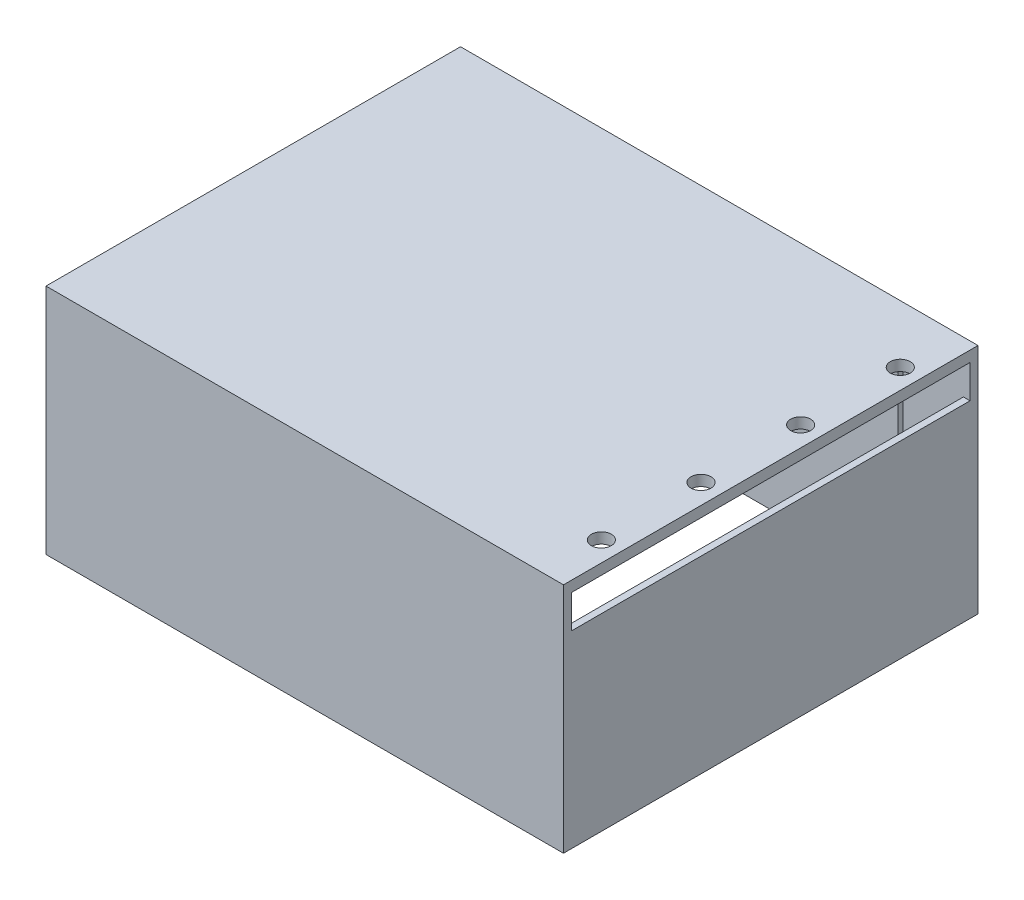
SolidWorks part; units mm, degrees
ref_plane "Front Plane" through (0, 0, 0) normal (0, 0, 1) x (1, 0, 0)
ref_plane "Top Plane" through (0, 0, 0) normal (0, 1, 0) x (1, 0, 0)
ref_plane "Right Plane" through (0, 0, 0) normal (1, 0, 0) x (0, 0, -1)
sketch "Sketch1" plane through (0, 0, 0) normal (0, 1, 0) x (1, 0, 0)
  line L1 (0, 0) -> (77.9, 0)
  line L2 (0, 0) -> (0, 62.4)
  line L3 (0, 62.4) -> (77.9, 62.4)
  line L4 (77.9, 0) -> (77.9, 62.4)
  dimension "D1" = 62.4
  dimension "D2" = 77.9
extrude "Boss-Extrude1" add sketch "Sketch1" along normal blind 35
sketch "Sketch4" plane through (0, 0, 0) normal (0, -1, 0) x (1, 0, 0)
  line L0 (75.9, -2) -> (2, -2)
  line L1 (2, -2) -> (2, -60.4)
  line L2 (2, -60.4) -> (75.9, -60.4)
  line L3 (75.9, -60.4) -> (75.9, -2)
  line L4 (0, 0) -> (0, -62.4)
  line L5 (0, -62.4) -> (77.9, -62.4)
  line L6 (77.9, -62.4) -> (77.9, 0)
  line L7 (77.9, 0) -> (0, 0)
  line L8 (0, 0) -> (0, -62.4)
  line L9 (0, -62.4) -> (77.9, -62.4)
  line L12 (77.9, 0) -> (0, 0) construction
  line L13 (77.9, -62.4) -> (77.9, 0) construction
  dimension "D1" = 0
  dimension "D2" = 2
extrude "Cut-Extrude1" cut sketch "Sketch4" against normal blind 33.39 contours L2 L3 L0 L1
sketch "Sketch6" plane through (0, 35, 0) normal (0, 1, 0) x (1, 0, 0)
  line L0 (2, 17.486) -> (16.1749, 17.486)
  line L1 (2, 2) -> (2, 60.4) construction
  line L2 (16.1749, 17.486) -> (16.1749, 7.5348)
  line L3 (16.1749, 7.5348) -> (0, 7.5348)
  line L4 (0, 62.4) -> (0, 0) construction
  line L5 (0, 7.5348) -> (0, 17.486)
  line L6 (0, 17.486) -> (2, 17.486)
sketch "Sketch7" plane through (0, 0, 0) normal (-1, 0, 0) x (0, 0, 1)
  line L0 (-48.9, 0) -> (-48.9, 5)
  line L1 (-62.4, 0) -> (0, 0) construction
  line L2 (-48.9, 0) -> (-48.9, -7.25) construction
  line L3 (-62.4, 35) -> (0, 35) construction
  line L5 (-42.3333, 35) -> (-42.3333, 0) construction
  line L6 (-35.7665, 0) -> (-35.7665, 5)
  line L7 (-48.9, 0) -> (-35.7665, 0)
  line L8 (-35.7665, 5) -> (-48.9, 5)
  dimension "D1" = 5
extrude "Cut-Extrude6" cut sketch "Sketch7" against normal blind 15
sketch "Sketch8" plane through (0, 35, 0) normal (0, 1, 0) x (1, 0, 0)
  circle A0 centre (10.2738, 54.1108) radius 1.75
  dimension "D1" = 3.5
sketch "Sketch9" plane through (0, 33.39, 0) normal (0, -1, 0) x (1, 0, 0)
  circle A0 centre (19.1575, -55.1585) radius 0.8
  circle A1 centre (69.9447, -11.9913) radius 0.8
  circle A2 centre (18.0145, -7.2415) radius 0.8
  circle A3 centre (69.9447, -39.9186) radius 0.8
  dimension "D1" = 1.6
  dimension "D2" = 1.6
  dimension "D3" = 1.6
  dimension "D4" = 1.6
sketch "Sketch11" plane through (0, 0, 0) normal (-1, 0, 0) x (0, 0, 1)
  line L0 (0, 35) -> (0, 0) construction
  line L1 (-17.4865, 0) -> (-7.53, 0)
  line L2 (-17.4865, 0) -> (-17.4865, 5.15)
  line L3 (-17.4865, 5.15) -> (-7.53, 5.15)
  line L4 (-7.53, 0) -> (-7.53, 5.15)
  line L5 (-35.7665, 0) -> (-35.7665, 5) construction
  line L6 (-35.7665, 0) -> (0, 0) construction
  dimension "D1" = 7.53
  dimension "D2" = 18.28
  dimension "D3" = 5.15
extrude "Cut-Extrude8" cut sketch "Sketch11" against normal blind 10
sketch "Sketch12" plane through (0, 0, 0) normal (-1, 0, 0) x (0, 0, 1)
  line L0 (-62.4, 0) -> (-48.9, 0) construction
  line L1 (-52.4, 25) -> (-35.4, 25)
  line L2 (-52.4, 25) -> (-52.4, 9)
  line L3 (-52.4, 9) -> (-35.4, 9)
  line L4 (-35.4, 25) -> (-35.4, 9)
  line L5 (-62.4, 35) -> (-62.4, 0) construction
  dimension "D1" = 9
  dimension "D2" = 16
  dimension "D3" = 17
  dimension "D4" = 10
extrude "Cut-Extrude9" cut sketch "Sketch12" against normal blind 10
sketch "Sketch14" plane through (77.9, 0, 0) normal (1, 0, 0) x (0, 0, -1)
  line L1 (61.2, 33.39) -> (1.2, 33.39)
  line L2 (61.2, 33.39) -> (61.2, 28.39)
  line L3 (61.2, 28.39) -> (1.2, 28.39)
  line L4 (1.2, 33.39) -> (1.2, 28.39)
  line L5 (31.2, 33.39) -> (31.2, 28.39) construction
  line L7 (60.4, 33.39) -> (2, 33.39) construction
  line L8 (31.2, 35) -> (31.2, 12.111) construction
  line L9 (0, 35) -> (62.4, 35) construction
  dimension "D1" = 60
  dimension "D2" = 5
  dimension "D3" = 0
extrude "Cut-Extrude10" cut sketch "Sketch14" against normal blind 10
sketch "Sketch16" plane through (0, 0, 0) normal (0, -1, 0) x (-1, 0, 0)
  line L0 (-77.9, 0) -> (-77.9, 62.4) construction
  line L1 (-67.9, 1.2) -> (-77.9, 1.2) construction
  line L2 (-76.9, 61.2) -> (-67.8234, 61.2)
  line L3 (-76.9, 61.2) -> (-76.9, 1.2)
  line L4 (-76.9, 1.2) -> (-67.8234, 1.2)
  line L5 (-67.8234, 61.2) -> (-67.8234, 1.2)
  line L6 (-67.9, 61.2) -> (-77.9, 61.2) construction
  dimension "D1" = 1
extrude "Cut-Extrude12" cut sketch "Sketch16" against normal up to surface (33.39 mm away)
sketch "Sketch15" plane through (0, 33.39, 0) normal (0, -1, 0) x (-1, 0, 0)
  line L0 (-74.9, 8.7) -> (-74.9, 23.7) construction
  line L1 (-74.9, 16.2) -> (-48.1021, 16.2) construction
  line L2 (-77.9, 31.2) -> (40.2463, 31.2) construction
  line L3 (-77.9, 61.2) -> (-77.9, 1.2) construction
  line L5 (-76.9, 61.2) -> (-76.9, 1.2) construction
  line L6 (-74.9, 38.7) -> (-74.9, 53.7) construction
  line L7 (-74.9, 46.2) -> (-46.556, 46.2) construction
  circle A0 centre (-74.9, 8.7) radius 1.5
  circle A1 centre (-74.9, 23.7) radius 1.5
  circle A2 centre (-74.9, 38.7) radius 1.5
  circle A3 centre (-74.9, 53.7) radius 1.5
  dimension "D1" = 3
  dimension "D2" = 3
  dimension "D4" = 2
  dimension "D5" = 3
  dimension "D6" = 3
  dimension "D7" = 15
  dimension "D3" = 15
  dimension "D8" = 15
  dimension "D9" = 15
extrude "Cut-Extrude11" cut sketch "Sketch15" against normal blind 10
sketch "Sketch17" plane through (2, 0, 0) normal (-1, 0, 0) x (0, 0, 1)
  line L0 (-62.4, 0) -> (0, 0) construction
  line L1 (-31.2, 0) -> (-31.2, 6.6797) construction
  line L2 (-31.2, 3.5) -> (-31.2, 1.5)
  line L3 (-33.7, 0) -> (-28.7, 0)
  line L7 (-33.7, 2.5) -> (-28.7, 2.5) construction
  arc A1 (-31.2, 3.5) -> (-31.2, 1.5) centre (-31.2, 2.5) ccw
  dimension "D1" = 2
sketch "Sketch18" plane through (0, 0, 0) normal (0, -1, 0) x (-1, 0, 0)
  line L0 (-76.9, 61.2) -> (-76.9, 1.2) construction
  line L5 (-76.9, 1.2) -> (-75.2943, 1.2)
  line L6 (-76.9, 1.2) -> (-76.9, 61.2)
  line L7 (-76.9, 61.2) -> (-75.2943, 61.2)
  line L8 (-75.2943, 1.2) -> (-75.2943, 61.2)
  line L9 (-76.9, 31.2) -> (-67.5467, 31.2) construction
  line L10 (-77.9, 31.2) -> (-62.8372, 31.2) construction
  line L11 (-77.9, 0) -> (-77.9, 62.4) construction
  line L13 (-76.9, 1.2) -> (-67.8234, 1.2) construction
extrude "Boss-Extrude2" add sketch "Sketch18" against normal blind 10
sketch "Sketch19" plane through (75.2943, 0, 0) normal (-1, 0, 0) x (0, 0, 1)
  line L0 (-62.4, 0) -> (0, 0) construction
  line L1 (-31.2, 0) -> (-31.2, 5) construction
  line L2 (-31.2, 2.5) -> (-18.5558, 2.5) construction
  line L3 (-31.2, 3.5) -> (-31.2, 1.5) construction
  line L4 (-31.2, 3.5) -> (-31.2, 1.5)
  arc A0 (-31.2, 1.5) -> (-31.2, 3.5) centre (-31.2, 2.5) ccw
  dimension "D1" = 2
  dimension "D2" = 2.5
revolve "Revolve2" add sketch "Sketch19" angle 360 about L3
revolve "Revolve4" add sketch "Sketch17" angle 360 about L2
